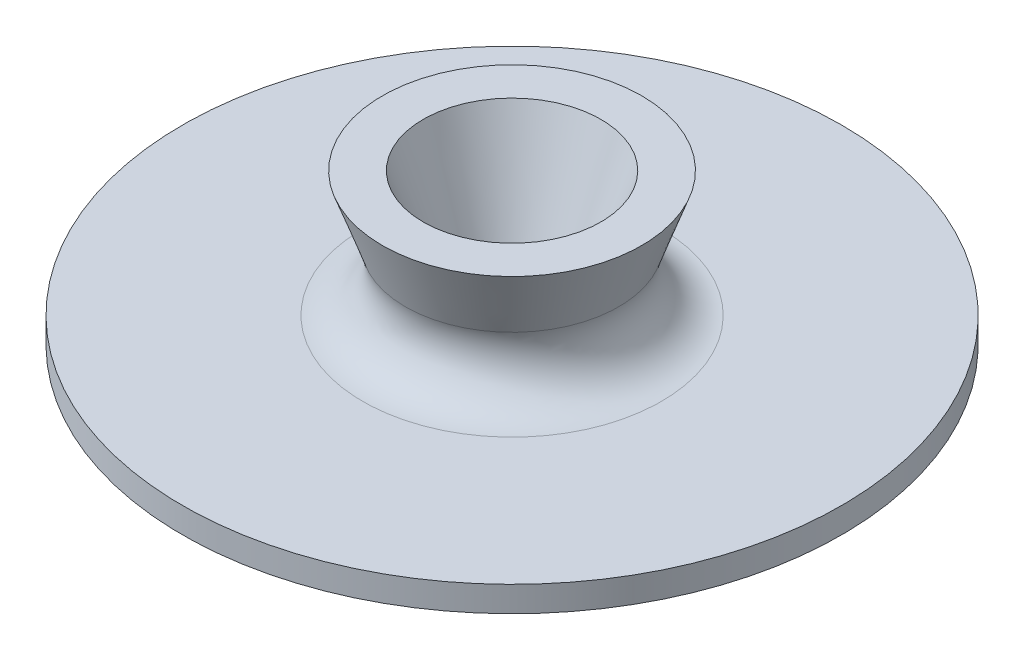
SolidWorks part; units mm, degrees
ref_plane "Front Plane" through (0, 0, 0) normal (0, 0, 1) x (1, 0, 0)
ref_plane "Top Plane" through (0, 0, 0) normal (0, 1, 0) x (1, 0, 0)
ref_plane "Right Plane" through (0, 0, 0) normal (1, 0, 0) x (0, 0, -1)
sketch "Sketch1" plane through (0, 0, 0) normal (0, 0, 1) x (1, 0, 0)
  line L0 (-18.7442, 0) -> (-72.6916, 0)
  line L1 (-72.6916, 0) -> (-72.6916, -5.6161)
  line L2 (-72.6916, -5.6161) -> (-13.3708, -5.6161)
  line L3 (-13.3708, -5.6161) -> (-9.7426, -15.775)
  line L4 (-9.7426, 0) -> (-4.1087, -15.775)
  line L5 (-4.1087, -15.775) -> (-9.7426, -15.775)
  line L6 (-9.7426, 0) -> (-19.6076, 27.622)
  line L7 (-19.6076, 27.622) -> (-28.6092, 27.622)
  line L8 (-28.6092, 27.622) -> (-18.7442, 0)
  line L9 (0, 0) -> (0, 52.9791) construction
revolve "Revolve1" add sketch "Sketch1" angle 360 about L9
fillet "Fillet1" radius 10 1 edges at (0, 0, -18.7442)
